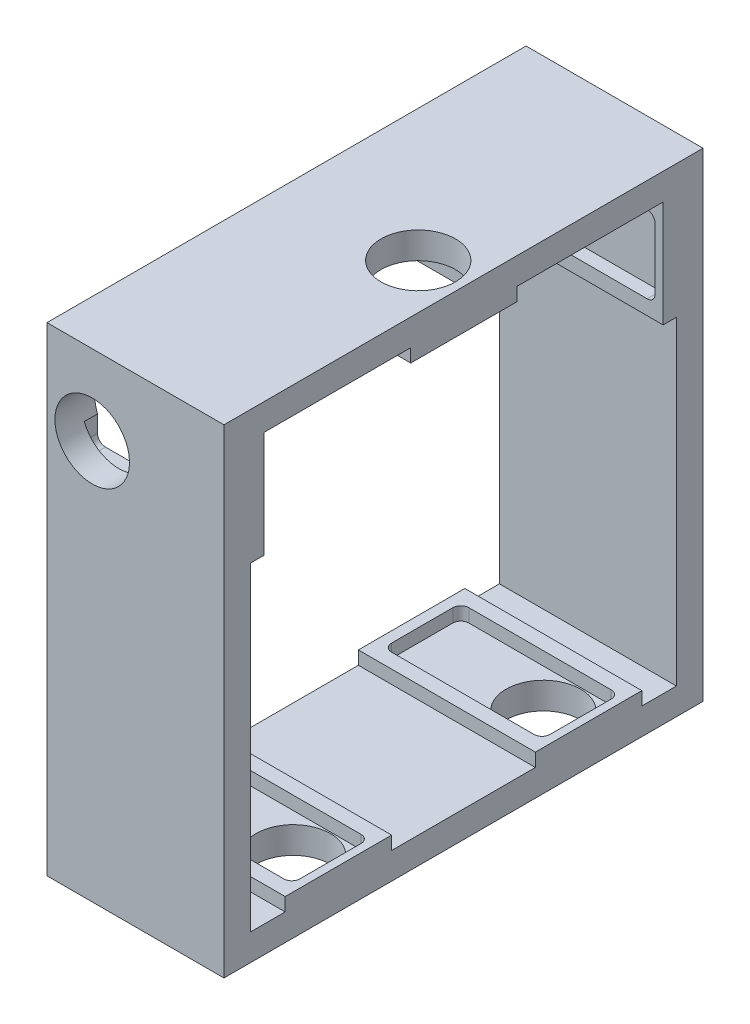
SolidWorks part; units mm, degrees
ref_plane "Front Plane" through (0, 0, 0) normal (0, 0, 1) x (1, 0, 0)
ref_plane "Top Plane" through (0, 0, 0) normal (0, 1, 0) x (1, 0, 0)
ref_plane "Right Plane" through (0, 0, 0) normal (1, 0, 0) x (0, 0, -1)
sketch "Sketch1" plane through (0, 0, 0) normal (0, 0, 1) x (1, 0, 0)
  line L1 (0, 0) -> (66.5, 0)
  line L2 (0, 0) -> (0, 180)
  line L3 (0, 180) -> (66.5, 180)
  line L4 (66.5, 0) -> (66.5, 180)
extrude "Boss-Extrude1" add sketch "Sketch1" along normal blind 180
sketch "Sketch3" plane through (0, 0, 0) normal (-1, 0, 0) x (0, 0, 1)
  line L9 (170, 10) -> (10, 10)
  line L10 (170, 10) -> (170, 170)
  line L11 (170, 170) -> (10, 170)
  line L12 (10, 10) -> (10, 170)
extrude "Cut-Extrude1" cut sketch "Sketch3" against normal blind 180
sketch "Sketch8" plane through (0, 0, 10) normal (0, 0, 1) x (1, 0, 0)
  line L0 (66.5, 170) -> (66.5, 10) construction
  line L1 (0, 170) -> (66.5, 170)
  line L2 (0, 170) -> (0, 130)
  line L3 (0, 130) -> (66.5, 130)
  line L4 (66.5, 170) -> (66.5, 130)
extrude "Boss-Extrude2" add sketch "Sketch8" along normal blind 5
sketch "Sketch10" plane through (0, 0, 170) normal (0, 0, -1) x (-1, 0, 0)
  line L0 (0, 10) -> (0, 170) construction
  line L1 (-66.5, 170) -> (0, 170)
  line L2 (-66.5, 170) -> (-66.5, 130)
  line L3 (-66.5, 130) -> (0, 130)
  line L4 (0, 170) -> (0, 130)
extrude "Boss-Extrude3" add sketch "Sketch10" along normal blind 5
sketch "Sketch5" plane through (0, 180, 0) normal (0, 1, 0) x (1, 0, 0)
  circle A1 centre (49.5, -90) radius 14
extrude "Cut-Extrude3" cut sketch "Sketch5" against normal blind 10
ref_plane "Plane4" through (0, 0, 0) normal (0, 0, -1) x (-1, 0, 0)
sketch "Sketch7" plane through (0, 0, 0) normal (0, -1, 0) x (1, 0, 0)
  line L1 (66.5, 170) -> (0, 170) construction
  line L2 (66.5, 10) -> (0, 10) construction
  circle A2 centre (49.5, 43) radius 14
  circle A3 centre (49.5, 137) radius 14
  dimension "D1" = 33
  dimension "D2" = 33
sketch "Sketch9" plane through (0, 0, 15) normal (0, 0, 1) x (1, 0, 0)
  line L5 (60.5, 164.5) -> (7.5, 164.5)
  line L12 (63.5, 161.5) -> (63.5, 138.5)
  line L13 (60.5, 135.5) -> (7.5, 135.5)
  line L14 (4.5, 161.5) -> (4.5, 138.5)
  arc A0 (7.5, 135.5) -> (4.5, 138.5) centre (7.5, 138.5) cw
  arc A5 (7.5, 164.5) -> (4.5, 161.5) centre (7.5, 161.5) ccw
  arc A6 (63.5, 161.5) -> (60.5, 164.5) centre (60.5, 161.5) ccw
  arc A7 (63.5, 138.5) -> (60.5, 135.5) centre (60.5, 138.5) cw
  point P3 (63.5, 150)
  dimension "D1" = 3
extrude "Cut-Extrude5" cut sketch "Sketch9" against normal blind 5
sketch "Sketch11" plane through (0, 0, 165) normal (0, 0, -1) x (-1, 0, 0)
  line L0 (-60.5, 164.5) -> (-7, 164.5)
  line L1 (-63.5, 161.5) -> (-63.5, 138.5)
  line L2 (-60.5, 135.5) -> (-7, 135.5)
  line L6 (-4, 161.5) -> (-4, 138.5)
  arc A1 (-7, 164.5) -> (-4, 161.5) centre (-7, 161.5) cw
  arc A2 (-7, 135.5) -> (-4, 138.5) centre (-7, 138.5) ccw
  arc A5 (-63.5, 138.5) -> (-60.5, 135.5) centre (-60.5, 138.5) ccw
  arc A6 (-60.5, 164.5) -> (-63.5, 161.5) centre (-60.5, 161.5) ccw
  point P8 (-57.5, 150)
  dimension "D1" = 3
  dimension "D2" = 3
extrude "Cut-Extrude6" cut sketch "Sketch11" against normal blind 5
sketch "Sketch12" plane through (0, 170, 0) normal (0, -1, 0) x (1, 0, 0)
  line L1 (66.5, 165) -> (66.5, 15) construction
  line L2 (66.5, 69.8335) -> (66.5, 109.8335)
  line L8 (66.5, 109.8335) -> (0, 109.8335)
  line L9 (66.5, 109.8335) -> (66.5, 69.8335)
  line L10 (66.5, 69.8335) -> (0, 69.8335)
  line L11 (0, 109.8335) -> (0, 69.8335)
  line L14 (60.5, 75.3335) -> (7, 75.3335)
  line L15 (63.5, 78.3335) -> (63.5, 101.3335)
  line L16 (60.5, 104.3335) -> (7, 104.3335)
  line L17 (4, 78.3335) -> (4, 101.3335)
  arc A0 (7, 104.3335) -> (4, 101.3335) centre (7, 101.3335) ccw
  arc A1 (63.5, 101.3335) -> (60.5, 104.3335) centre (60.5, 101.3335) ccw
  arc A2 (63.5, 78.3335) -> (60.5, 75.3335) centre (60.5, 78.3335) cw
  arc A3 (7, 75.3335) -> (4, 78.3335) centre (7, 78.3335) cw
  point P6 (63.5, 89.8335)
  point P7 (63.5, 89.8335)
  point P8 (57.5, 90)
  point P19 (57.5, 90)
  point P22 (66.5, 89.8335)
  dimension "D1" = 3
extrude "Boss-Extrude8" add sketch "Sketch12" along normal blind 5
sketch "Sketch13" plane through (0, 10, 0) normal (0, 1, 0) x (1, 0, 0)
  line L8 (66.5, -10) -> (0, -10) construction
  line L9 (66.5, -170) -> (0, -170) construction
  line B0 (0, -63) -> (66.5, -63)
  line B1 (0, -63) -> (0, -23)
  line B2 (0, -23) -> (66.5, -23)
  line B3 (66.5, -63) -> (66.5, -23)
  line B4 (7, -57.5) -> (60.5, -57.5)
  line B5 (4, -54.5) -> (4, -31.5)
  line B6 (7, -28.5) -> (60.5, -28.5)
  line B7 (63.5, -54.5) -> (63.5, -31.5)
  arc B8 (63.5, -54.5) -> (60.5, -57.5) centre (60.5, -54.5) cw
  arc B9 (63.5, -31.5) -> (60.5, -28.5) centre (60.5, -31.5) ccw
  arc B10 (4, -31.5) -> (7, -28.5) centre (7, -31.5) cw
  arc B11 (7, -57.5) -> (4, -54.5) centre (7, -54.5) cw
  line B12 (0, -157) -> (0, -117)
  line B13 (0, -157) -> (66.5, -157)
  line B14 (0, -117) -> (66.5, -117)
  line B15 (66.5, -157) -> (66.5, -117)
  line B16 (7, -151.5) -> (60.5, -151.5)
  line B17 (4, -148.5) -> (4, -125.5)
  line B18 (7, -122.5) -> (60.5, -122.5)
  line B19 (63.5, -148.5) -> (63.5, -125.5)
  arc B20 (63.5, -148.5) -> (60.5, -151.5) centre (60.5, -148.5) cw
  arc B21 (63.5, -125.5) -> (60.5, -122.5) centre (60.5, -125.5) ccw
  arc B22 (4, -125.5) -> (7, -122.5) centre (7, -125.5) cw
  arc B23 (7, -151.5) -> (4, -148.5) centre (7, -148.5) cw
  dimension "D1" = 13
  dimension "D2" = 13
sketch_block_instance "Bloco2-1"
sketch_block "Bloco2" parameters "D1"=3
sketch_block_instance "Bloco3-1"
sketch_block "Bloco3"
sketch "Sketch15" plane through (0, 0, 0) normal (0, 0, -1) x (-1, 0, 0)
  circle A0 centre (-17, 150) radius 14
extrude "Cut-Extrude7" cut sketch "Sketch15" against normal blind 200
extrude "Corte-extrusão1" cut sketch "Sketch7" against normal blind 10
extrude "Ressalto-extrusão1" add sketch "Sketch13" along normal blind 5
